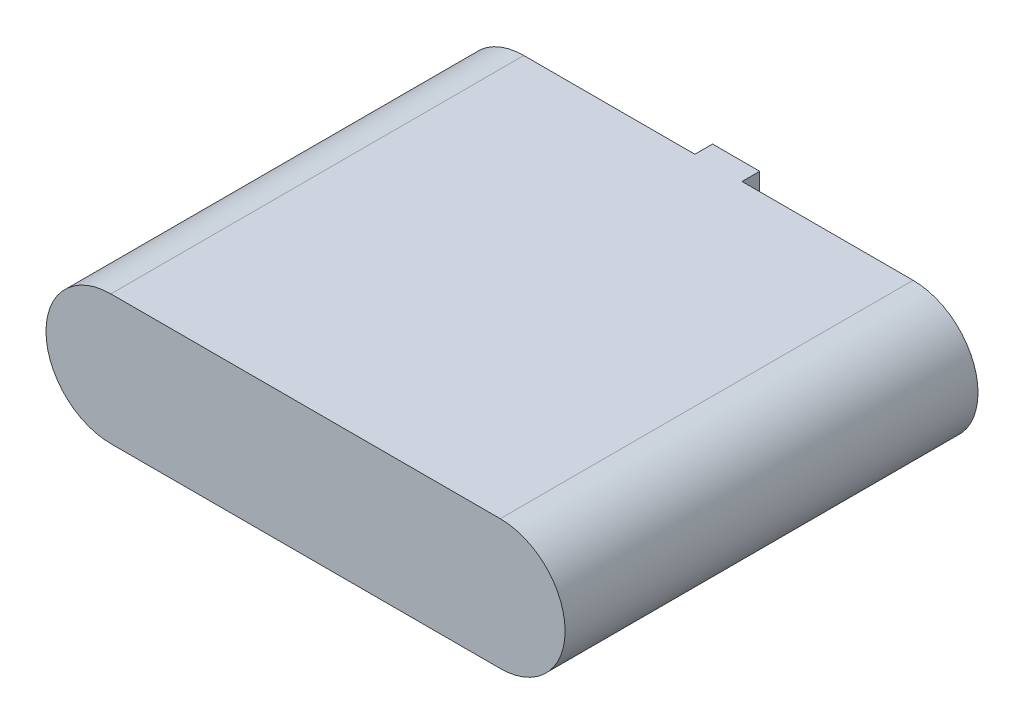
SolidWorks part; units mm, degrees
material "电池材料"
ref_plane "前视基准面" through (0, 0, 0) normal (0, 0, 1) x (1, 0, 0)
ref_plane "上视基准面" through (0, 0, 0) normal (0, 1, 0) x (1, 0, 0)
ref_plane "右视基准面" through (0, 0, 0) normal (1, 0, 0) x (0, 0, -1)
other "Configuration Table"
sketch "草图1" plane through (0, 0, 0) normal (0, 0, 1) x (1, 0, 0)
  line L0 (0, 0) -> (66, 0) construction
  line L1 (0, 11) -> (66, 11)
  line L2 (0, -11) -> (66, -11)
  arc A0 (0, 11) -> (0, -11) centre (0, 0) ccw
  arc A1 (66, -11) -> (66, 11) centre (66, 0) ccw
  point P3 (33, 0)
  dimension "D1" = 11
  dimension "D2" = 66
extrude "凸台-拉伸1" add sketch "草图1" along normal blind 70
sketch "草图2" plane through (0, 0, 0) normal (0, 0, -1) x (-1, 0, 0)
  line L0 (-66, 11) -> (0, 11) construction
  line L1 (-37, 11) -> (-29, 11)
  line L2 (-37, 11) -> (-37, 7)
  line L3 (-37, 7) -> (-29, 7)
  line L4 (-29, 11) -> (-29, 7)
  line L5 (-66, 11) -> (0, 11)
  point P6 (-33, 11)
  point P7 (-33, 11)
  line M5 (0, 11) -> (-66, 11)
  dimension "D1" = 4
  dimension "D2" = 8
extrude "凸台-拉伸2" add sketch "草图2" along normal blind 3 contours L4 L2 L3 M5
sketch "草图3" plane through (0, 11, 0) normal (0, 1, 0) x (1, 0, 0)
  line L0 (33, -70) -> (33, 3) construction
  line L1 (66, -70) -> (0, -70) construction
  line L2 (29, 3) -> (37, 3) construction
